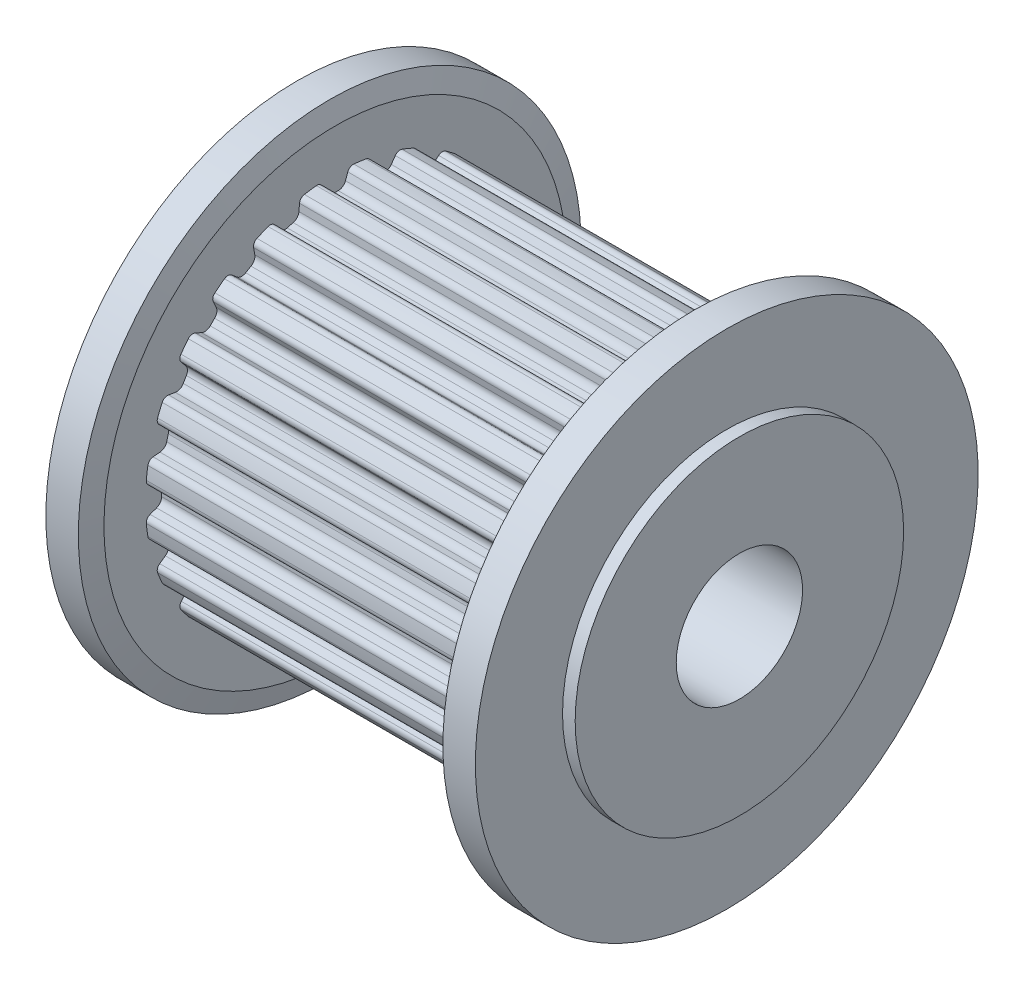
SolidWorks part; units mm, degrees
ref_plane "前视基准面" through (0, 0, 0) normal (0, 0, 1) x (1, 0, 0)
ref_plane "上视基准面" through (0, 0, 0) normal (0, 1, 0) x (1, 0, 0)
ref_plane "右视基准面" through (0, 0, 0) normal (1, 0, 0) x (0, 0, -1)
sketch "草图1" plane through (0, 0, 0) normal (0, 0, 1) x (1, 0, 0)
  line L0 (-9, 6.5) -> (-7, 6.5)
  line L1 (-7, 6.5) -> (-7, 7.51)
  line L2 (-7, 7.51) -> (7, 7.51)
  line L3 (0, 0) -> (0, 7.51) construction
  line L4 (-9, 6.5) -> (-9, 0)
  line L5 (9, 6.5) -> (9, 0)
  line L6 (7, 6.5) -> (7, 7.51)
  line L7 (9, 6.5) -> (7, 6.5)
  line L8 (-9, 0) -> (9, 0)
  dimension "D1" = 6.5
  dimension "D2" = 7.51
  dimension "D3" = 14
  dimension "D4" = 18
revolve "旋转1" add sketch "草图1" angle 360 about L8
sketch "草图3" plane through (0, 0, 0) normal (1, 0, 0) x (0, 0, -1)
  line L0 (0, 0) -> (0, 7.51) construction
  line L1 (-0.335, 6.8618) -> (-0.5632, 7.4889)
  line L2 (0.5632, 7.4889) -> (0.335, 6.8618)
  arc A0 (0.5632, 7.4889) -> (-0.5632, 7.4889) centre (0, 0) ccw
  circle A1 centre (0, 0) radius 7.51 construction
  arc A2 (0.335, 6.8618) -> (-0.335, 6.8618) centre (0, 0) ccw
  dimension "D4" = 0.64
  dimension "D1" = 0.67
  dimension "D2" = 20
  dimension "D3" = 20
extrude "切除-拉伸3" cut sketch "草图3" against normal mid plane 14
fillet "圆角3" radius 0.23 2 edges at (0, 7.4889, -0.5632) (0, 7.4889, 0.5632)
fillet "圆角4" radius 0.3 2 edges at (0, 6.8618, -0.335) (0, 6.8618, 0.335)
pattern_circular "阵列(圆周)2" count 24 over 360 about axis through (0, 0, 0) along (1, 0, 0) of "圆角3", "切除-拉伸3", "圆角4"
sketch "草图4" plane through (0, 0, 0) normal (0, 0, 1) x (1, 0, 0)
  line L0 (-8.5, 9.95) -> (-8.5, 6.5)
  line L1 (-7, 6.5) -> (-9, 6.5) construction
  line L2 (8.5, 9.95) -> (8.5, 6.5)
  line L3 (-8.5, 9.95) -> (-7.2144, 9.95)
  line L4 (-7.2144, 9.95) -> (-7, 9.15)
  line L5 (-7, 9.15) -> (-7, 6.5)
  line L6 (-7, 6.5) -> (-8.5, 6.5)
  line L7 (-7, 7.51) -> (-7, -7.51) construction
  line L9 (0, 0) -> (0, 9.52) construction
  line L11 (-9, 0) -> (9, 0) construction
  line L12 (-9, 6.5) -> (-9, -6.5) construction
  line L13 (9, -6.5) -> (9, 6.5) construction
  line L14 (7, 9.15) -> (7, 6.5)
  line L15 (7, 6.5) -> (8.5, 6.5)
  line L17 (7.2144, 9.95) -> (7, 9.15)
  line L18 (8.5, 9.95) -> (7.2144, 9.95)
  dimension "D1" = 1.5
  dimension "D2" = 15
  dimension "D3" = 9.95
  dimension "D4" = 0.8
revolve "旋转2" add sketch "草图4" angle 360 about L11
sketch "草图5" plane through (0, 0, 0) normal (0, 0, 1) x (1, 0, 0)
  line L0 (9, -6.5) -> (9, 6.5) construction
  line L1 (9, 0) -> (15.5, 0)
  line L2 (9, 0) -> (9, 5.5)
  line L3 (9, 5.5) -> (15.5, 5.5)
  line L4 (15.5, 0) -> (15.5, 5.5)
  dimension "D1" = 5.5
  dimension "D2" = 6.5
revolve "旋转3" [suppressed] add sketch "草图5" angle 360 about L1
sketch "草图37" [suppressed] plane through (0, 0, 0) normal (0, 0, 1) x (1, 0, 0)
  line L0 (-5, 0) -> (5, 0) construction
  line L1 (-5, 8.95) -> (-3, 8.95)
  line L2 (-5, 8.95) -> (-5, 5.5)
  line L3 (-5, 5.5) -> (-3, 5.5)
  line L4 (-3, 8.95) -> (-3, 5.5)
  line L5 (-5, 5.5) -> (-5, -5.5) construction
  line L6 (5, -5.5) -> (5, 5.5) construction
  line L7 (0, 0) -> (0, 7.8967) construction
  line L8 (3, 8.95) -> (3, 5.5)
  line L9 (5, 5.5) -> (3, 5.5)
  line L10 (5, 8.95) -> (3, 8.95)
  line L11 (5, 8.95) -> (5, 5.5)
  dimension "D1" = 7
  dimension "D2" = 6.5
  dimension "D3" = 9.95
  dimension "D4" = 2
revolve "切除-旋转5" [suppressed] cut sketch "草图37" angle 360 about L0
sketch "草图6" [suppressed] plane through (0, 0, 0) normal (0, 0, 1) x (1, 0, 0)
  line L0 (-4.5, 5.95) -> (-4.5, 3)
  line L1 (-3, 3) -> (-5, 3) construction
  line L3 (-4.5, 5.95) -> (-3.2144, 5.95)
  line L4 (-3.2144, 5.95) -> (-3, 5.15)
  line L5 (-3, 5.15) -> (-3, 3)
  line L6 (-3, 3) -> (-4.5, 3)
  line L8 (3, 0) -> (3, 5.15)
  line L9 (3, 5.15) -> (3.2278, 6)
  line L10 (3.2278, 6) -> (11.5, 6)
  line L11 (11.5, 6) -> (11.5, 0)
  line L12 (11.5, 0) -> (3, 0)
  line L14 (-5, 0) -> (5, 0) construction
  line L15 (-5, 3) -> (-5, -3) construction
  line L16 (5, -3) -> (5, 3) construction
  dimension "D1" = 1.5
  dimension "D2" = 15
  dimension "D3" = 0.8
  dimension "D4" = 9.95
  dimension "D5" = 5.5
  dimension "D6" = 15
  dimension "D7" = 16.5
  dimension "D8" = 7
revolve "旋转4" [suppressed] add sketch "草图6" angle 360 about L14
sketch "草图7" plane through (-9, 0, 0) normal (-1, 0, 0) x (0, 0, 1)
  circle A0 centre (0, 0) radius 2.5
  dimension "D1" = 5
extrude "切除-拉伸4" cut sketch "草图7" against normal through all
sketch "草图31" [suppressed] plane through (0, 0, 0) normal (0, 1, 0) x (1, 0, 0)
  circle A0 centre (8.5, 0) radius 1.29
  dimension "D2" = 2.58
  dimension "D1" = 8.5
extrude "切除-拉伸21" [suppressed] cut sketch "草图31" along normal through all
cosmetic thread "装饰螺纹线9" [suppressed] parameters "D2"=3
sketch "草图32" [suppressed] plane through (0, 0, 0) normal (0, 1, 0) x (1, 0, 0)
  line L0 (0, 0) -> (-5, 0) construction
  line L1 (-5, 5.5) -> (-5, -5.5) construction
ref_plane "基准面5" [suppressed] through (0, 0, 0) normal (0, -0.5, -0.866) x (1, 0, 0)
sketch "草图33" [suppressed] plane through (0, 0, 0) normal (0, -0.5, -0.866) x (1, 0, 0)
  circle A0 centre (8.5, 0) radius 1.29
  dimension "D2" = 2.58
  dimension "D1" = 8.5
extrude "切除-拉伸22" [suppressed] cut sketch "草图33" along normal through all
cosmetic thread "装饰螺纹线10" [suppressed] parameters "D2"=3
sketch "草图16" [suppressed] plane through (-5, 0, 0) normal (-1, 0, 0) x (0, 0, 1)
  line L0 (-1.5, 0) -> (-1.5, 2.9)
  line L1 (-1.5, 2.9) -> (1.5, 2.9)
  line L2 (1.5, 2.9) -> (1.5, 0)
  arc A0 (-1.5, 0) -> (1.5, 0) centre (0, 0) ccw
  dimension "D2" = 2.5
  dimension "D1" = 3
  dimension "D3" = 3.9
extrude "切除-拉伸10" [suppressed] cut sketch "草图16" against normal through all
sketch "草图27" [suppressed] plane through (11.5, 0, 0) normal (1, 0, 0) x (0, 0, -1)
  circle A0 centre (0, 0) radius 5
  dimension "D1" = 10
extrude "切除-拉伸19" [suppressed] cut sketch "草图27" against normal blind 5
sketch "草图29" [suppressed] plane through (0, 0, 0) normal (0, 0, 1) x (1, 0, 0)
  line L0 (-5, 5) -> (-2, 5)
  line L1 (-5, 8) -> (-5, -8) construction
  line L2 (-2, 5) -> (-2, 4)
  line L3 (-2, 4) -> (2, 4)
  line L4 (2, 4) -> (2, 5)
  line L5 (2, 5) -> (5, 5)
  line L6 (5, -8) -> (5, 8) construction
  line L7 (5, 5) -> (5, 0)
  line L8 (5, 0) -> (-5, 0)
  line L9 (-5, 0) -> (-5, 5)
  dimension "D1" = 4.5
  dimension "D2" = 3
  dimension "D3" = 3
  dimension "D4" = 5
  dimension "D5" = 2.5
revolve "切除-旋转1" [suppressed] cut sketch "草图29" angle 360 about L8
sketch "草图38" plane through (0, 0, 0) normal (0, 0, 1) x (1, 0, 0)
  line L0 (-9, 6.5) -> (-9, -6.5) construction
  line L1 (-9, 0) -> (-4, 0)
  line L2 (-9, 0) -> (-9, 5)
  line L3 (-9, 5) -> (-4, 5)
  line L4 (-4, 0) -> (-4, 5)
  dimension "D1" = 5
  dimension "D2" = 5
revolve "切除-旋转6" [suppressed] cut sketch "草图38" angle 360 about L1
sketch "草图36" [suppressed] plane through (0, 0, 0) normal (0, 0, 1) x (1, 0, 0)
  line L0 (0, 0) -> (-5, 0) construction
  line L1 (-3, 4.275) -> (-5, 4.275)
  line L2 (-3, 4.275) -> (-3, 5.95)
  line L3 (-3, 5.95) -> (-5, 5.95)
  line L4 (-5, 4.275) -> (-5, 5.95)
  line L5 (-5, 3) -> (-5, -3) construction
  dimension "D1" = 7.51
  dimension "D2" = 9.95
  dimension "D3" = 7
  dimension "D4" = 2
revolve "切除-旋转4" [suppressed] cut sketch "草图36" angle 360 about L0
sketch "草图35" [suppressed] plane through (0, 0, 0) normal (0, 0, 1) x (1, 0, 0)
  line L0 (-5, 0) -> (0, 0) construction
  line L1 (3, 4.275) -> (5, 4.275)
  line L2 (3, 4.275) -> (3, 5.95)
  line L3 (3, 5.95) -> (5, 5.95)
  line L4 (5, 4.275) -> (5, 5.95)
  line L5 (-5, 3) -> (-5, -3) construction
  dimension "D1" = 7.51
  dimension "D2" = 9.95
  dimension "D3" = 2
  dimension "D4" = 7
revolve "切除-旋转3" [suppressed] cut sketch "草图35" angle 360 about L0
sketch "草图39" [suppressed] plane through (0, 0, 0) normal (0, 0, 1) x (1, 0, 0)
  line L0 (-1000, 0) -> (49000, 0) construction
  line L1 (4.5, -8.95) -> (4.5, 8.95) construction
  line L2 (-4.5, 8.95) -> (4.5, 8.95)
  line L3 (-4.5, 8.95) -> (-4.5, 8)
  line L4 (-4.5, 8) -> (4.5, 8)
  line L5 (4.5, 8.95) -> (4.5, 8)
  dimension "D1" = 8
revolve "切除-旋转7" [suppressed] cut sketch "草图39" angle 360 about L0
sketch "草图40" [suppressed] plane through (0, 0, 0) normal (0, 0, 1) x (1, 0, 0)
  line L0 (11.5, 4.29) -> (5.5, 4.29)
  line L1 (11.5, -4.5) -> (11.5, 4.5) construction
  line L2 (5.5, 4.29) -> (4.7249, 3)
  line L3 (4.7249, 3) -> (11.5, 3)
  line L4 (11.5, 3) -> (11.5, 4.29)
  dimension "D1" = 59
  dimension "D2" = 1.29
  dimension "D3" = 6
  dimension "D4" = 3
revolve "切除-旋转8" [suppressed] cut sketch "草图40" angle 360 about L3
cosmetic thread "装饰螺纹线11" [suppressed] parameters "D2"=3
pattern_circular "阵列(圆周)3" [suppressed] count 4 over 360
sketch "草图41" [suppressed] plane through (0, 0, 0) normal (0, 0, 1) x (1, 0, 0)
  line L0 (11.5, 4.29) -> (5.5, 4.29)
  line L1 (11.5, -4.5) -> (11.5, 4.5) construction
  line L2 (5.5, 4.29) -> (4.7249, 3)
  line L3 (4.7249, 3) -> (11.5, 3)
  line L4 (11.5, 3) -> (11.5, 4.29)
  dimension "D1" = 59
  dimension "D2" = 3
  dimension "D3" = 1.29
  dimension "D4" = 6
revolve "切除-旋转9" [suppressed] cut sketch "草图41" angle 360 about L3
cosmetic thread "装饰螺纹线12" [suppressed] parameters "D2"=3
pattern_circular "阵列(圆周)4" [suppressed] count 3 over 360
sketch "草图42" [suppressed] plane through (0, 0, 0) normal (0, 0, 1) x (1, 0, 0)
  line L0 (11.5, 4.29) -> (5.5, 4.29)
  line L1 (11.5, -4.5) -> (11.5, 4.5) construction
  line L2 (5.5, 4.29) -> (4.7249, 3)
  line L3 (4.7249, 3) -> (11.5, 3)
  line L4 (11.5, 3) -> (11.5, 4.29)
  dimension "D1" = 59
  dimension "D2" = 3
  dimension "D3" = 1.29
  dimension "D4" = 6
revolve "切除-旋转10" [suppressed] cut sketch "草图42" angle 360 about L3
cosmetic thread "装饰螺纹线13" [suppressed] parameters "D2"=3
pattern_circular "阵列(圆周)5" [suppressed] count 6 over 360
sketch "草图43" [suppressed] plane through (0, 0, 0) normal (0, 0, 1) x (1, 0, 0)
  line L0 (11.5, -4.55) -> (11.5, 4.55) construction
  line L1 (11.5, 3) -> (-5, 3)
  line L2 (11.5, 3) -> (11.5, 4.5)
  line L3 (11.5, 4.5) -> (-5, 4.5)
  line L4 (-5, 3) -> (-5, 4.5)
  line L5 (-5, 5.5) -> (-5, -5.5) construction
  dimension "D1" = 3
  dimension "D2" = 1.5
revolve "切除-旋转12" [suppressed] cut sketch "草图43" angle 360 about L1
pattern_circular "阵列(圆周)6" [suppressed] count 4 over 360
sketch "草图44" [suppressed] plane through (0, 0, 0) normal (0, 0, 1) x (1, 0, 0)
  line L0 (11.5, -4.55) -> (11.5, 4.55) construction
  line L1 (11.5, 3) -> (-5, 3)
  line L2 (11.5, 3) -> (11.5, 4.5)
  line L3 (11.5, 4.5) -> (-5, 4.5)
  line L4 (-5, 3) -> (-5, 4.5)
  line L5 (-5, 5.5) -> (-5, -5.5) construction
  dimension "D1" = 3
  dimension "D2" = 1.5
revolve "切除-旋转13" [suppressed] cut sketch "草图44" angle 360 about L1
pattern_circular "阵列(圆周)7" [suppressed] count 3 over 360
sketch "草图45" [suppressed] plane through (0, 0, 0) normal (0, 0, 1) x (1, 0, 0)
  line L0 (11.5, -4.55) -> (11.5, 4.55) construction
  line L1 (11.5, 3) -> (-5, 3)
  line L2 (11.5, 3) -> (11.5, 4.45)
  line L3 (11.5, 4.45) -> (-5, 4.45)
  line L4 (-5, 3) -> (-5, 4.45)
  line L5 (-5, 5.5) -> (-5, -5.5) construction
  dimension "D1" = 3
  dimension "D2" = 1.45
revolve "切除-旋转14" [suppressed] cut sketch "草图45" angle 360 about L1
pattern_circular "阵列(圆周)12" [suppressed] count 6 over 360
sketch "草图46" [suppressed] plane through (0, 0, 0) normal (0, 0, 1) x (1, 0, 0)
  line L0 (-5, 4.65) -> (8, 4.65)
  line L1 (-5, 5.5) -> (-5, -5.5) construction
  line L2 (8, 4.65) -> (8, 6.25)
  line L3 (8, 6.25) -> (11.5, 6.25)
  line L4 (11.5, -4.55) -> (11.5, 4.55) construction
  line L5 (11.5, 6.25) -> (11.5, 3)
  line L6 (11.5, 3) -> (-5, 3)
  line L7 (-5, 3) -> (-5, 4.65)
  dimension "D1" = 3
  dimension "D2" = 1.65
  dimension "D3" = 3.25
  dimension "D4" = 3.5
revolve "切除-旋转15" [suppressed] cut sketch "草图46" angle 360 about L6
pattern_circular "阵列(圆周)13" [suppressed] count 4 over 360
sketch "草图47" [suppressed] plane through (0, 0, 0) normal (0, 0, 1) x (1, 0, 0)
  line L0 (-5, 4.65) -> (8, 4.65)
  line L1 (-5, 5.5) -> (-5, -5.5) construction
  line L2 (8, 4.65) -> (8, 6.25)
  line L3 (8, 6.25) -> (11.5, 6.25)
  line L4 (11.5, -4.55) -> (11.5, 4.55) construction
  line L5 (11.5, 6.25) -> (11.5, 3)
  line L6 (11.5, 3) -> (-5, 3)
  line L7 (-5, 3) -> (-5, 4.65)
  dimension "D1" = 3
  dimension "D2" = 1.65
  dimension "D3" = 3.25
  dimension "D4" = 3.5
revolve "切除-旋转16" [suppressed] cut sketch "草图47" angle 360 about L6
pattern_circular "阵列(圆周)14" [suppressed] count 3 over 360
sketch "草图48" [suppressed] plane through (0, 0, 0) normal (0, 0, 1) x (1, 0, 0)
  line L0 (-5, 4.65) -> (8, 4.65)
  line L1 (-5, 5.5) -> (-5, -5.5) construction
  line L2 (8, 4.65) -> (8, 6.25)
  line L3 (8, 6.25) -> (11.5, 6.25)
  line L4 (11.5, -4.55) -> (11.5, 4.55) construction
  line L5 (11.5, 6.25) -> (11.5, 3)
  line L6 (11.5, 3) -> (-5, 3)
  line L7 (-5, 3) -> (-5, 4.65)
  dimension "D1" = 3
  dimension "D2" = 1.65
  dimension "D3" = 3.25
  dimension "D4" = 3.5
revolve "切除-旋转17" [suppressed] cut sketch "草图48" angle 360 about L6
pattern_circular "阵列(圆周)15" [suppressed] count 6 over 360
sketch "Sketch1" plane through (-9, 0, 0) normal (-1, 0, 0) x (0, 0, 1)
  point P0 (0, 0)
  line B0 (1.5347, 1.2825) -> (-1.5357, 1.2812)
  line B1 (-2.1469, 1.281) -> (2.1458, 1.2827)
  line B2 (-1.5357, 1.2812) -> (-2.1469, 1.281)
  line B3 (-1.5357, 1.2812) -> (-2.1469, 1.281)
  line B4 (-2.1469, 1.281) -> (2.1458, 1.2827)
  line B5 (-1.5357, 1.2812) -> (-2.1469, 1.281)
  arc B6 (2.1458, 1.2827) -> (-2.1469, 1.281) centre (0, 0) ccw
  arc B7 (-2.1469, 1.281) -> (2.1458, 1.2827) centre (0, 0) ccw
  arc B8 (-1.5357, 1.2812) -> (1.5347, 1.2825) centre (0, 0) ccw
  arc B9 (-1.5357, 1.2812) -> (1.5347, 1.2825) centre (0, 0) ccw
  arc B10 (-1.5357, 1.2812) -> (1.5347, 1.2825) centre (0, 0) ccw
sketch_block_instance "Stepper_Shaft_D_Profile-1"
sketch_block "Stepper_Shaft_D_Profile"
